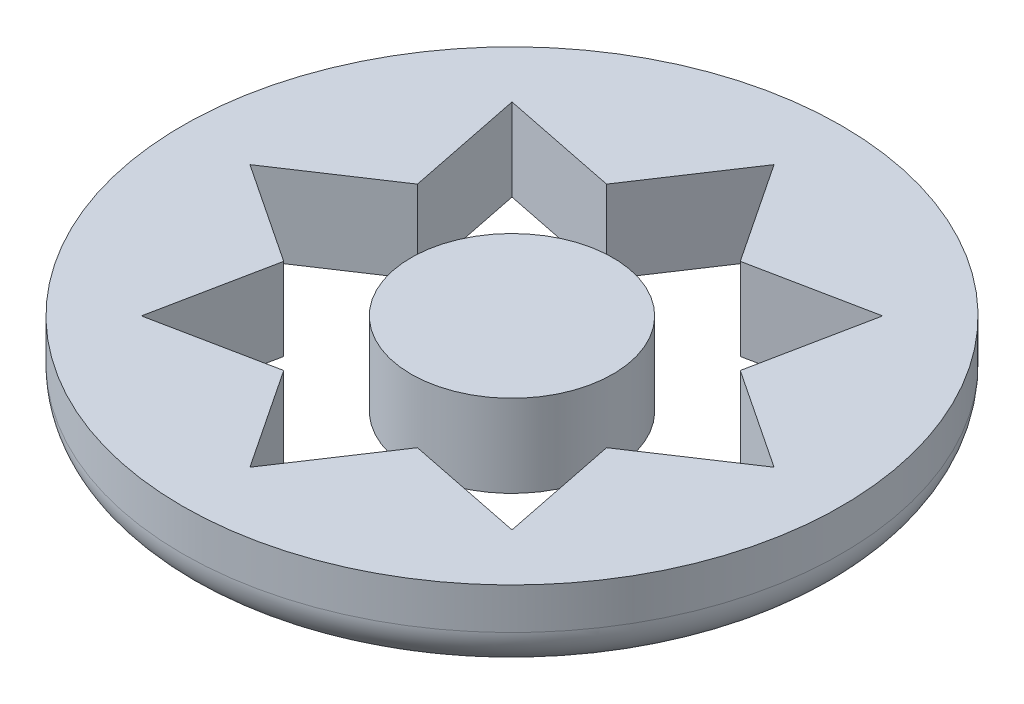
SolidWorks part; units mm, degrees
ref_plane "Front Plane" through (0, 0, 0) normal (0, 0, 1) x (1, 0, 0)
ref_plane "Top Plane" through (0, 0, 0) normal (0, 1, 0) x (1, 0, 0)
ref_plane "Right Plane" through (0, 0, 0) normal (1, 0, 0) x (0, 0, -1)
sketch "Sketch1" plane through (0, 0, 0) normal (0, 1, 0) x (1, 0, 0)
  line L0 (0, 0) -> (0, 7.4856) construction
  line L1 (0, 0) -> (3.4051, 8.2205) construction
  line L2 (0, 0) -> (-3.5263, 8.5132) construction
  line L3 (-1.5307, 3.6955) -> (0, 6) construction
  line L4 (0, 6) -> (1.5307, 3.6955) construction
  line L19 (1.5307, 3.6955) -> (4.2426, 4.2426) construction
  line L20 (4.2426, 4.2426) -> (3.6955, 1.5307) construction
  line L21 (3.6955, 1.5307) -> (6, 0) construction
  line L22 (6, 0) -> (3.6955, -1.5307) construction
  line L23 (3.6955, -1.5307) -> (4.2426, -4.2426) construction
  line L24 (4.2426, -4.2426) -> (1.5307, -3.6955) construction
  line L25 (1.5307, -3.6955) -> (0, -6) construction
  line L26 (0, -6) -> (-1.5307, -3.6955) construction
  line L27 (-1.5307, -3.6955) -> (-4.2426, -4.2426) construction
  line L28 (-4.2426, -4.2426) -> (-3.6955, -1.5307) construction
  line L29 (-3.6955, -1.5307) -> (-6, 0) construction
  line L30 (-6, 0) -> (-3.6955, 1.5307) construction
  line L31 (-3.6955, 1.5307) -> (-4.2426, 4.2426) construction
  line L32 (-4.2426, 4.2426) -> (-1.5307, 3.6955) construction
  line L33 (-3.9182, 1.623) -> (-4.4982, 4.4982)
  line L34 (-4.4982, 4.4982) -> (-1.623, 3.9182)
  line L35 (-1.623, 3.9182) -> (0, 6.3615)
  line L36 (0, 6.3615) -> (1.623, 3.9182)
  line L37 (1.623, 3.9182) -> (4.4982, 4.4982)
  line L38 (4.4982, 4.4982) -> (3.9182, 1.623)
  line L39 (3.9182, 1.623) -> (6.3615, 0)
  line L40 (6.3615, 0) -> (3.9182, -1.623)
  line L41 (3.9182, -1.623) -> (4.4982, -4.4982)
  line L42 (4.4982, -4.4982) -> (1.623, -3.9182)
  line L43 (1.623, -3.9182) -> (0, -6.3615)
  line L44 (0, -6.3615) -> (-1.623, -3.9182)
  line L45 (-1.623, -3.9182) -> (-4.4982, -4.4982)
  line L46 (-4.4982, -4.4982) -> (-3.9182, -1.623)
  line L47 (-3.9182, -1.623) -> (-6.3615, 0)
  line L48 (-6.3615, 0) -> (-3.9182, 1.623)
  circle A1 centre (0, 0) radius 4 construction
  circle A2 centre (0, 0) radius 6 construction
  circle A3 centre (0, 0) radius 8
  point P23 (0, -1.4856)
  point P37 (0, 0)
  dimension "D1" = 12
  dimension "D2" = 8
  dimension "D3" = 16
  dimension "D4" = 22.5
  dimension "D5" = 22.5
  dimension "D6" = 8
  dimension "D7" = 0.2
extrude "Boss-Extrude1" add sketch "Sketch1" along normal blind 2
fillet "Fillet1" radius 1 1 edges at (0, 0, 8)
sketch "Sketch2" plane through (0, 2, 0) normal (0, 1, 0) x (1, 0, 0)
  circle A0 centre (0, 0) radius 2.45
  dimension "D1" = 4.9
extrude "Boss-Extrude2" add sketch "Sketch2" against normal up to surface (2 mm away) separate body up to face at (0, 0, 7)
